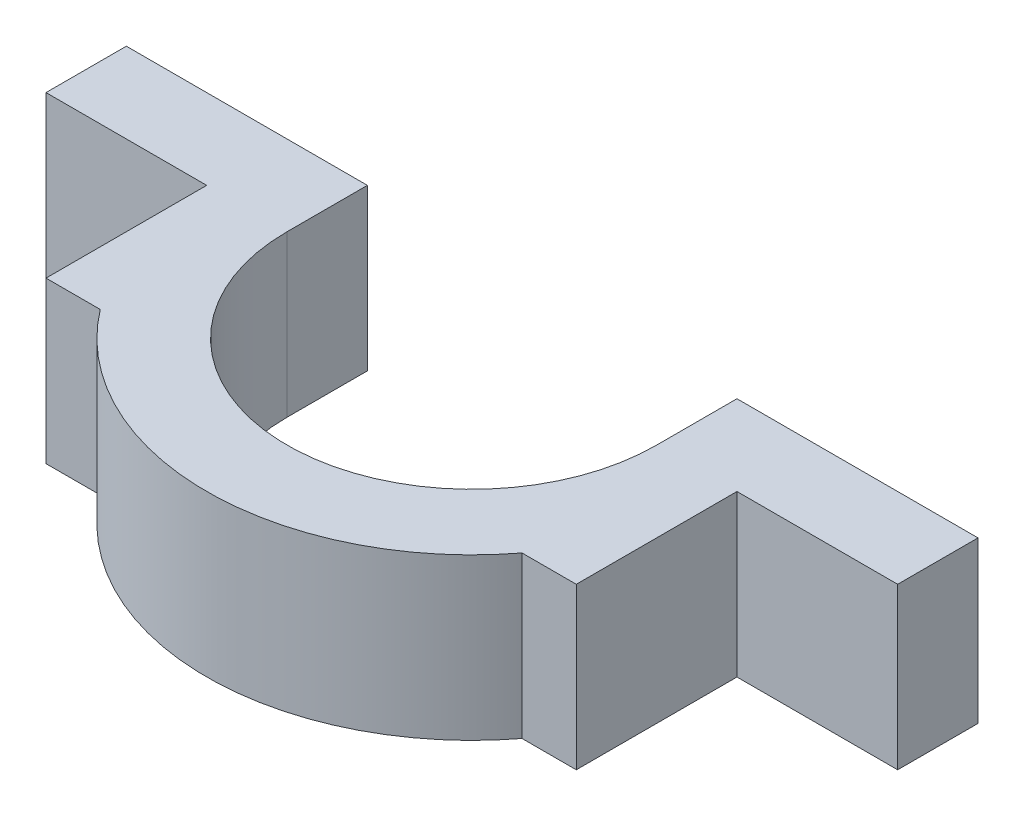
SolidWorks part; units mm, degrees
ref_plane "Спереди" through (0, 0, 0) normal (0, 0, 1) x (1, 0, 0)
ref_plane "Сверху" through (0, 0, 0) normal (0, 1, 0) x (1, 0, 0)
ref_plane "Справа" through (0, 0, 0) normal (1, 0, 0) x (0, 0, -1)
other "Configuration Table"
sketch "Эскиз1" plane through (0, 0, 0) normal (0, 1, 0) x (1, 0, 0)
  line L0 (0, 0) -> (79.5301, 0) construction
  line L1 (-16.5, 0) -> (-16.5, -10)
  line L2 (-16.5, -10) -> (-13.1244, -10)
  line L3 (16.5, -10) -> (16.5, 0)
  line L4 (16.5, 0) -> (26.5, 0)
  line L5 (26.5, 0) -> (26.5, 5)
  line L6 (26.5, 5) -> (11.5, 5)
  line L7 (-26.5, 5) -> (-26.5, 0)
  line L8 (-26.5, 0) -> (-16.5, 0)
  line L9 (-11.5, 0) -> (-11.5, 5)
  line L10 (11.5, 0) -> (11.5, 5)
  line L11 (-11.5, 5) -> (-26.5, 5)
  line L12 (13.1244, -10) -> (16.5, -10)
  arc A0 (-11.5, 0) -> (11.5, 0) centre (0, 0) ccw
  arc A1 (-13.1244, -10) -> (13.1244, -10) centre (0, 0) ccw
  circle A3 centre (0, 0) radius 11.5 construction
  circle A4 centre (0, 0) radius 16.5 construction
  point P1 (16.5, 0)
  point P19 (10.9975, 3.3623)
  dimension "D1" = 23
  dimension "D3" = 10
  dimension "D4" = 5
  dimension "D5" = 10
  dimension "D6" = 10
  dimension "D7" = 33
  dimension "D2" = 5
extrude "Бобышка-Вытянуть1" add sketch "Эскиз1" along normal blind 10
